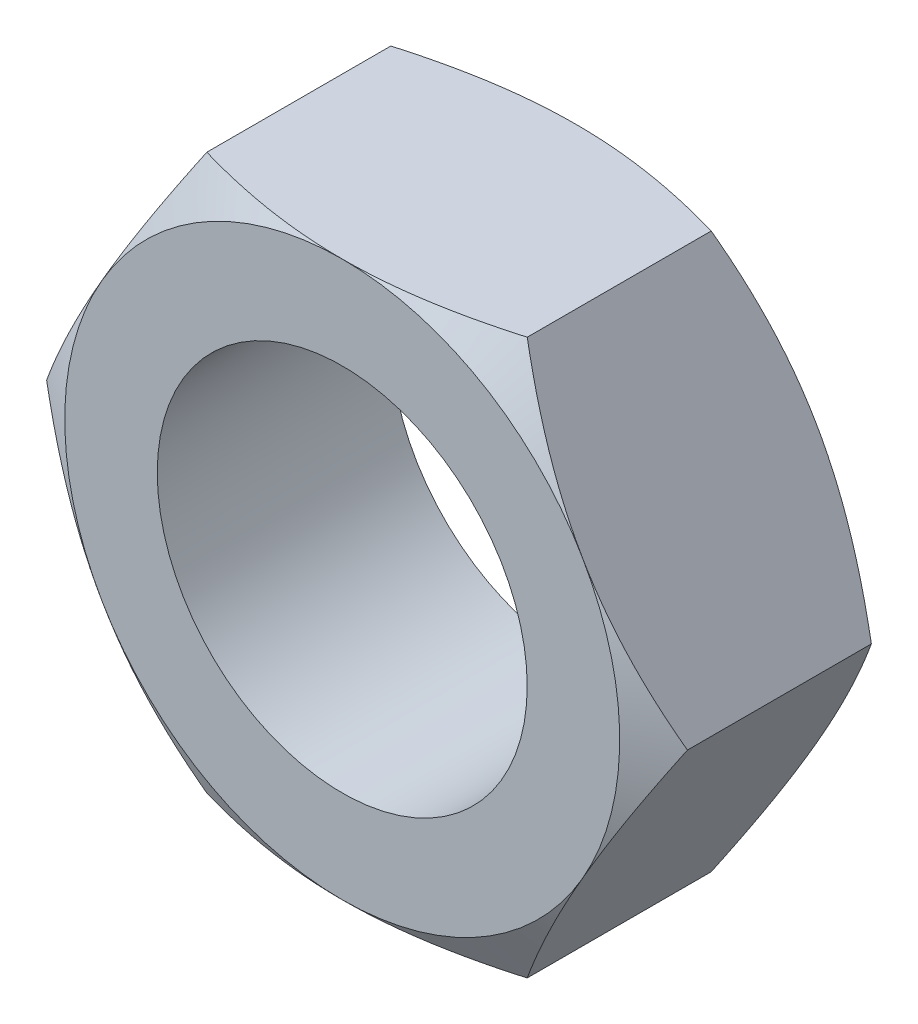
SolidWorks part; units mm, degrees
ref_plane "Front Plane" through (0, 0, 0) normal (0, 0, 1) x (1, 0, 0)
ref_plane "Top Plane" through (0, 0, 0) normal (0, 1, 0) x (1, 0, 0)
ref_plane "Right Plane" through (0, 0, 0) normal (1, 0, 0) x (0, 0, -1)
sketch "Sketch1" plane through (0, 0, 0) normal (0, 0, 1) x (1, 0, 0)
  line L1 (13.8564, 0) -> (6.9282, 12)
  line L2 (6.9282, 12) -> (-6.9282, 12)
  line L3 (-6.9282, 12) -> (-13.8564, 0)
  line L4 (-13.8564, 0) -> (-6.9282, -12)
  line L5 (-6.9282, -12) -> (6.9282, -12)
  line L6 (6.9282, -12) -> (13.8564, 0)
  circle A0 centre (0, 0) radius 12 construction
  dimension "D1" = 24
extrude "Boss-Extrude1" add sketch "Sketch1" along normal blind 10.1
sketch "Sketch2" plane through (0, 0, 10.1) normal (0, 0, 1) x (1, 0, 0)
  circle A0 centre (0, 0) radius 12
extrude "Cut-Extrude1" cut sketch "Sketch2" against normal through all draft 60 flip side to cut
sketch "Sketch8" plane through (0, 0, 0) normal (0, 0, -1) x (-1, 0, 0)
  circle A0 centre (0, 0) radius 8
extrude "Cut-Extrude4" cut sketch "Sketch8" against normal through all
sketch "Sketch9" plane through (0, 0, 0) normal (0, 0, 1) x (1, 0, 0)
  circle A0 centre (0, 0) radius 12
extrude "Cut-Extrude6" cut sketch "Sketch9" along normal through all draft 60 flip side to cut
